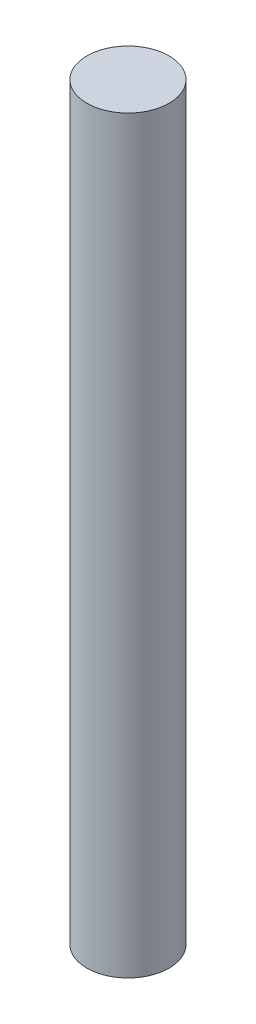
SolidWorks part; units mm, degrees
material "6061 Alloy"
ref_plane "Front Plane" through (0, 0, 0) normal (0, 0, 1) x (1, 0, 0)
ref_plane "Top Plane" through (0, 0, 0) normal (0, 1, 0) x (1, 0, 0)
ref_plane "Right Plane" through (0, 0, 0) normal (1, 0, 0) x (0, 0, -1)
sketch "Sketch1" plane through (0, 0, 0) normal (0, 1, 0) x (1, 0, 0)
  circle A1 centre (0, 0) radius 4.7625
  dimension "D1" = 9.525
extrude "Boss-Extrude1" add sketch "Sketch1" along normal blind 86.825
